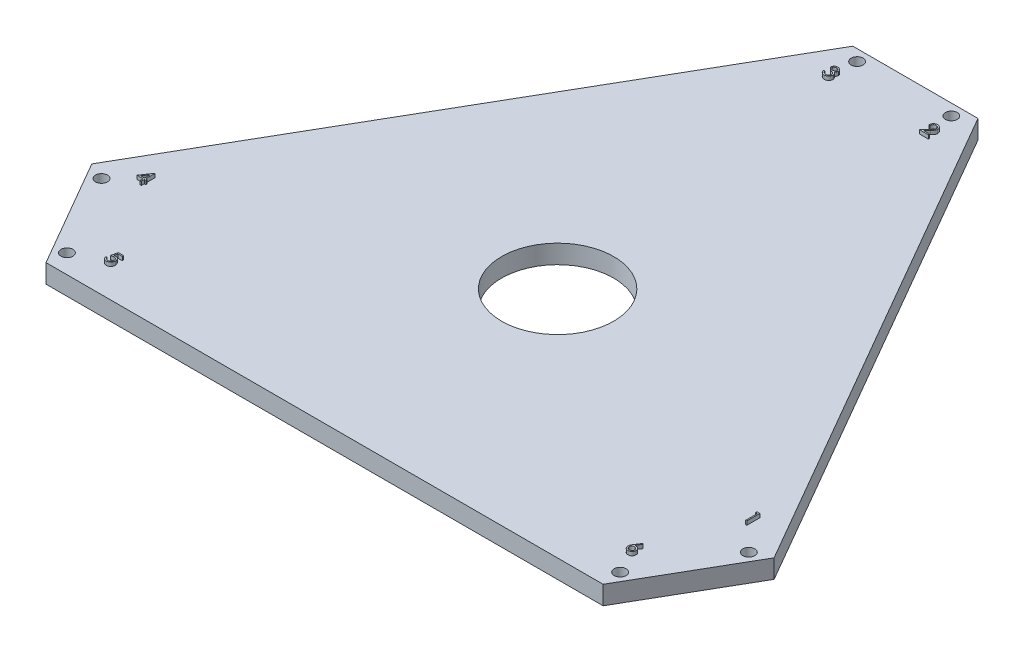
SolidWorks part; units mm, degrees
ref_plane "Front Plane" through (0, 0, 0) normal (0, 0, 1) x (1, 0, 0)
ref_plane "Top Plane" through (0, 0, 0) normal (0, 1, 0) x (1, 0, 0)
ref_plane "Right Plane" through (0, 0, 0) normal (1, 0, 0) x (0, 0, -1)
sketch "Sketch1" plane through (0, 0, 0) normal (0, 1, 0) x (1, 0, 0)
  line L0 (-74.5712, -62.3979) -> (74.5712, -62.3979)
  line L1 (74.5712, -62.3979) -> (91.3238, -33.3815)
  line L2 (91.3238, -33.3815) -> (16.7526, 95.7795)
  line L3 (16.7526, 95.7795) -> (-16.7526, 95.7795)
  line L4 (-16.7526, 95.7795) -> (-91.3238, -33.3815)
  line L5 (-91.3238, -33.3815) -> (-74.5712, -62.3979)
  arc A0 (0, 15) -> (0, -15) centre (0, 0) ccw
  arc A1 (0, -15) -> (0, 15) centre (0, 0) ccw
  arc A2 (86.6542, -37.0695) -> (86.6542, -33.8695) centre (86.6542, -35.4695) ccw
  arc A3 (86.6542, -33.8695) -> (86.6542, -37.0695) centre (86.6542, -35.4695) ccw
  arc A4 (74.0446, -58.91) -> (74.0446, -55.71) centre (74.0446, -57.31) ccw
  arc A5 (74.0446, -55.71) -> (74.0446, -58.91) centre (74.0446, -57.31) ccw
  arc A6 (-74.0446, -58.91) -> (-74.0446, -55.71) centre (-74.0446, -57.31) ccw
  arc A7 (-74.0446, -55.71) -> (-74.0446, -58.91) centre (-74.0446, -57.31) ccw
  arc A8 (-86.6542, -37.0695) -> (-86.6542, -33.8695) centre (-86.6542, -35.4695) ccw
  arc A9 (-86.6542, -33.8695) -> (-86.6542, -37.0695) centre (-86.6542, -35.4695) ccw
  arc A10 (-12.6096, 94.3795) -> (-12.6096, 91.1795) centre (-12.6096, 92.7795) ccw
  arc A11 (-12.6096, 91.1795) -> (-12.6096, 94.3795) centre (-12.6096, 92.7795) ccw
  arc A12 (12.6096, 94.3795) -> (12.6096, 91.1795) centre (12.6096, 92.7795) ccw
  arc A13 (12.6096, 91.1795) -> (12.6096, 94.3795) centre (12.6096, 92.7795) ccw
extrude "Boss-Extrude1" add sketch "Sketch1" along normal blind 5
sketch "Sketch2" plane through (0, 5, 0) normal (0, 1, 0) x (1, 0, 0)
  text T0 "1"
  text T1 "2"
  text T2 "3"
  text T3 "4"
  text T4 "5"
  text T5 "6"
extrude "Boss-Extrude2" add sketch "Sketch2" along normal blind 1
